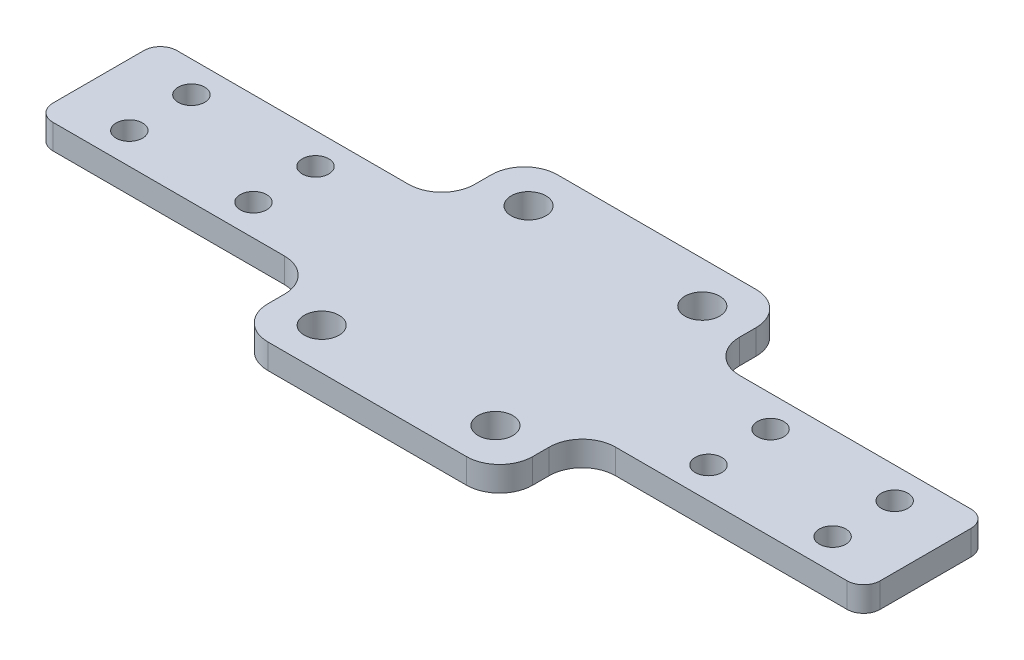
SolidWorks part; units mm, degrees
ref_plane "前视基准面" through (0, 0, 0) normal (0, 0, 1) x (1, 0, 0)
ref_plane "上视基准面" through (0, 0, 0) normal (0, 1, 0) x (1, 0, 0)
ref_plane "右视基准面" through (0, 0, 0) normal (1, 0, 0) x (0, 0, -1)
other "Configuration Table"
sketch "草图1" plane through (0, 0, 0) normal (0, 1, 0) x (1, 0, 0)
  line L1 (-50, -7.5) -> (50, -7.5)
  line L2 (-50, -7.5) -> (-50, 7.5)
  line L3 (-50, 7.5) -> (50, 7.5)
  line L4 (50, -7.5) -> (50, 7.5)
  line L5 (-50, -7.5) -> (50, 7.5) construction
  line L6 (-50, 7.5) -> (50, -7.5) construction
  point P0 (0, 0)
  dimension "D1" = 100
  dimension "D2" = 15
extrude "凸台-拉伸1" add sketch "草图1" along normal blind 3
sketch "草图2" plane through (0, 3, 0) normal (0, 1, 0) x (1, 0, 0)
  line L1 (-16, 17.5) -> (16, 17.5)
  line L2 (-16, 17.5) -> (-16, -17.5)
  line L3 (-16, -17.5) -> (16, -17.5)
  line L4 (16, 17.5) -> (16, -17.5)
  line L5 (0, 0) -> (0, 17.5) construction
  dimension "D1" = 32
  dimension "D2" = 35
  dimension "D3" = 17.5
extrude "凸台-拉伸2" add sketch "草图2" against normal blind 3
sketch "草图3" plane through (0, 3, 0) normal (0, 1, 0) x (1, 0, 0)
  line L0 (0, 0) -> (-50, 0) construction
  line L2 (0, 0) -> (0, 10) construction
  line L4 (-35, 10) -> (-35, -10) construction
  circle A0 centre (-42.5, 3.75) radius 1.6
  circle A1 centre (-42.5, -3.75) radius 1.6
  circle A2 centre (-27.5, -3.75) radius 1.6
  circle A3 centre (-27.5, 3.75) radius 1.6
  circle A4 centre (42.5, -3.75) radius 1.6
  circle A5 centre (42.5, 3.75) radius 1.6
  circle A6 centre (27.5, -3.75) radius 1.6
  circle A7 centre (27.5, 3.75) radius 1.6
  dimension "D2" = 3.2
  dimension "D1" = 35
  dimension "D3" = 3.75
  dimension "D4" = 7.5
  dimension "D5" = 10
extrude "切除-拉伸1" cut sketch "草图3" against normal through all
sketch "草图4" plane through (0, 3, 0) normal (0, 1, 0) x (1, 0, 0)
  line L0 (0, 0) -> (0, 10.9579) construction
  line L1 (0, 0) -> (-19.9516, 0) construction
  circle A0 centre (-10.5, 12.5) radius 2.1
  circle A1 centre (-10.5, -12.5) radius 2.1
  circle A2 centre (10.5, -12.5) radius 2.1
  circle A3 centre (10.5, 12.5) radius 2.1
  dimension "D1" = 4.2
  dimension "D2" = 25
  dimension "D3" = 21
extrude "切除-拉伸2" cut sketch "草图4" against normal through all
fillet "圆角1" radius 4 8 edges at (-16, 1.5, 17.5) (16, 1.5, 17.5) (16, 1.5, -17.5) (-16, 1.5, -17.5) (-16, 1.5, -7.5) (16, 1.5, -7.5) (16, 1.5, 7.5) (-16, 1.5, 7.5)
fillet "圆角2" radius 2 4 edges at (-50, 1.5, 7.5) (-50, 1.5, -7.5) (50, 1.5, 7.5) (50, 1.5, -7.5)
